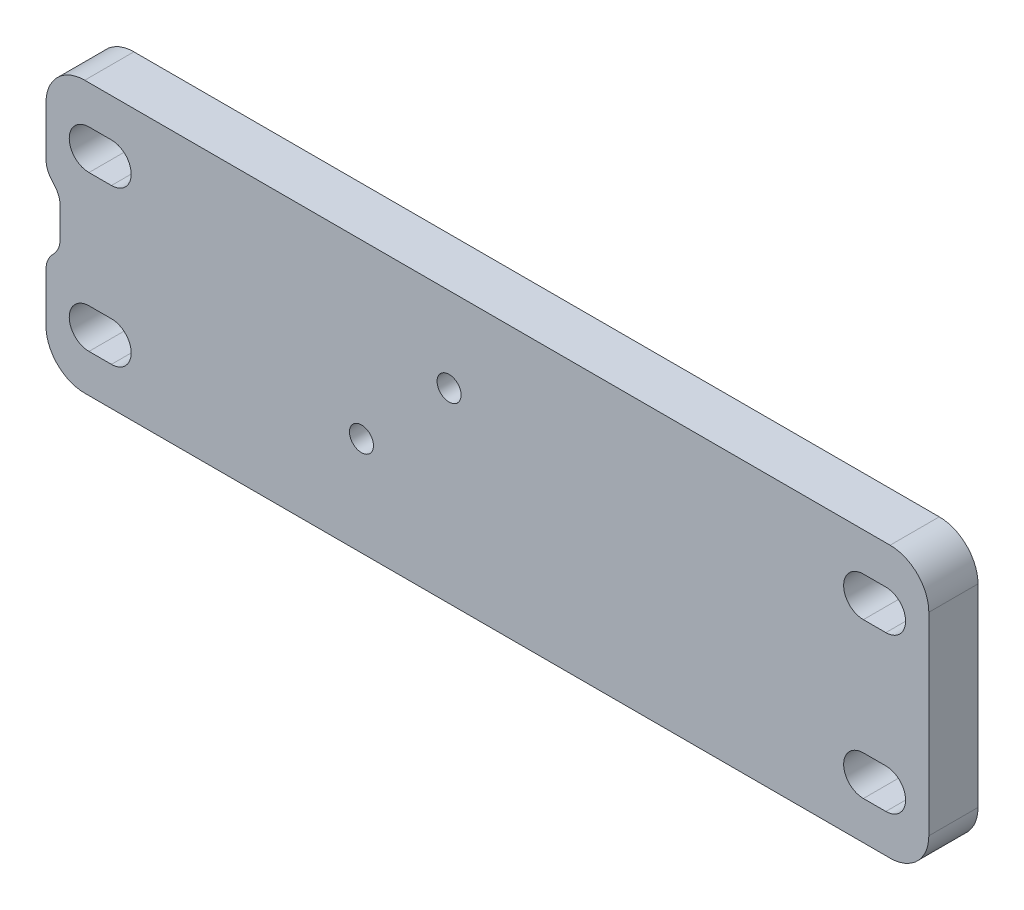
SolidWorks part; units mm, degrees
ref_plane "Front Plane" through (0, 0, 0) normal (0, 0, 1) x (1, 0, 0)
ref_plane "Top Plane" through (0, 0, 0) normal (0, 1, 0) x (1, 0, 0)
ref_plane "Right Plane" through (0, 0, 0) normal (1, 0, 0) x (0, 0, -1)
sketch "Sketch1" plane through (0, 0, 0) normal (0, 0, 1) x (1, 0, 0)
  line L30 (231.1006, 220.3839) -> (231.1006, 226.718)
  line L31 (231.1006, 239.0497) -> (231.1006, 245.3839)
  line L32 (232.9316, 234.718) -> (232.9316, 231.0497)
  line L35 (232.1444, 229.0239) -> (231.8879, 228.7438)
  line L43 (231.8879, 237.0239) -> (232.1444, 236.7438)
  line L46 (340.1006, 215.3839) -> (236.1006, 215.3839)
  line L49 (339.5506, 220.3339) -> (336.6506, 220.3339)
  line L50 (236.6506, 220.3339) -> (239.5506, 220.3339)
  line L51 (239.5506, 225.4339) -> (236.6506, 225.4339)
  line L52 (336.6506, 225.4339) -> (339.5506, 225.4339)
  line L56 (239.5506, 240.3339) -> (236.6506, 240.3339)
  line L57 (336.6506, 240.3339) -> (339.5506, 240.3339)
  line L59 (339.5506, 245.4339) -> (336.6506, 245.4339)
  line L60 (236.6506, 245.4339) -> (239.5506, 245.4339)
  line L61 (236.1006, 250.3839) -> (340.1006, 250.3839)
  line L78 (345.1006, 245.3839) -> (345.1006, 220.3839)
  arc A41 (231.1006, 220.3839) -> (236.1006, 215.3839) centre (236.1006, 220.3839) ccw
  arc A49 (231.8879, 228.7438) -> (231.1006, 226.718) centre (234.1006, 226.718) ccw
  arc A50 (232.9316, 234.718) -> (232.1444, 236.7438) centre (229.9316, 234.718) ccw
  arc A51 (232.1444, 229.0239) -> (232.9316, 231.0497) centre (229.9316, 231.0497) ccw
  arc A56 (236.6506, 225.4339) -> (236.6506, 220.3339) centre (236.6506, 222.8839) ccw
  arc A57 (239.5506, 220.3339) -> (239.5506, 225.4339) centre (239.5506, 222.8839) ccw
  circle A58 centre (271.8376, 228.1539) radius 1.55
  arc A61 (236.1006, 250.3839) -> (231.1006, 245.3839) centre (236.1006, 245.3839) ccw
  arc A66 (231.1006, 239.0497) -> (231.8879, 237.0239) centre (234.1006, 239.0497) ccw
  arc A69 (239.5506, 240.3339) -> (239.5506, 245.4339) centre (239.5506, 242.8839) ccw
  arc A70 (236.6506, 245.4339) -> (236.6506, 240.3339) centre (236.6506, 242.8839) ccw
  arc A98 (340.1006, 215.3839) -> (345.1006, 220.3839) centre (340.1006, 220.3839) ccw
  arc A104 (336.6506, 225.4339) -> (336.6506, 220.3339) centre (336.6506, 222.8839) ccw
  arc A105 (339.5506, 220.3339) -> (339.5506, 225.4339) centre (339.5506, 222.8839) ccw
  arc A125 (345.1006, 245.3839) -> (340.1006, 250.3839) centre (340.1006, 245.3839) ccw
  arc A138 (339.5506, 240.3339) -> (339.5506, 245.4339) centre (339.5506, 242.8839) ccw
  arc A139 (336.6506, 245.4339) -> (336.6506, 240.3339) centre (336.6506, 242.8839) ccw
  circle A146 centre (283.1506, 239.4679) radius 1.55
extrude "Boss-Extrude1" add sketch "Sketch1" along normal blind 6.35
